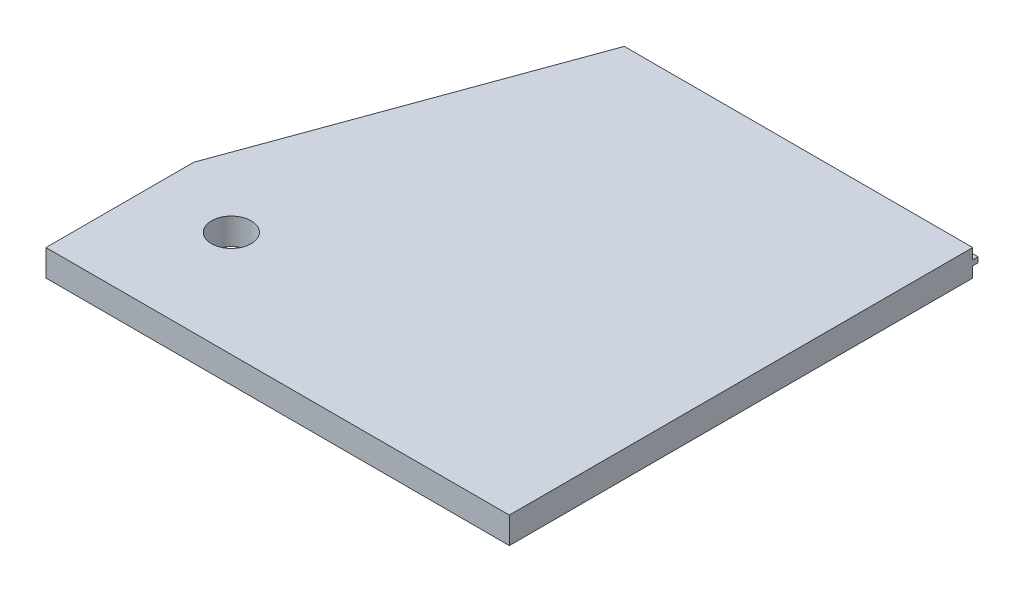
SolidWorks part; units mm, degrees
ref_plane "Front Plane" through (0, 0, 0) normal (0, 0, 1) x (1, 0, 0)
ref_plane "Top Plane" through (0, 0, 0) normal (0, 1, 0) x (1, 0, 0)
ref_plane "Right Plane" through (0, 0, 0) normal (1, 0, 0) x (0, 0, -1)
sketch "Sketch1" plane through (0, 0, 0) normal (0, 1, 0) x (1, 0, 0)
  line L0 (0, 55.76) -> (43.41, 175)
  line L1 (0, 0) -> (175, 0)
  line L2 (0, 0) -> (0, 55.76)
  line L3 (43.41, 175) -> (175, 175)
  line L4 (175, 0) -> (175, 175)
  dimension "D1" = 55.76
  dimension "D2" = 175
  dimension "D3" = 131.59
  dimension "D4" = 69.996
extrude "Boss-Extrude1" add sketch "Sketch1" along normal blind 10
sketch "Sketch2" plane through (0, 0, -175) normal (0, 0, -1) x (-1, 0, 0)
  line L0 (-175, 10) -> (-175, 0) construction
  line L1 (-175, 6) -> (-43.41, 6)
  line L2 (-175, 6) -> (-175, 4)
  line L3 (-175, 4) -> (-43.41, 4)
  line L4 (-43.41, 6) -> (-43.41, 4)
  line L5 (-43.41, 10) -> (-43.41, 0) construction
  point P8 (-175, 5)
  point P9 (-175, 5)
  dimension "D1" = 2
extrude "Boss-Extrude2" add sketch "Sketch2" along normal blind 2
sketch "Sketch3" plane through (0, 10, 0) normal (0, 1, 0) x (1, 0, 0)
  line L0 (0, 55.76) -> (0, 0) construction
  line L2 (0, 0) -> (175, 0) construction
  circle A0 centre (30, 40) radius 7.5
  dimension "D1" = 15
  dimension "D2" = 30
  dimension "D3" = 40
extrude "Cut-Extrude1" cut sketch "Sketch3" against normal through all
